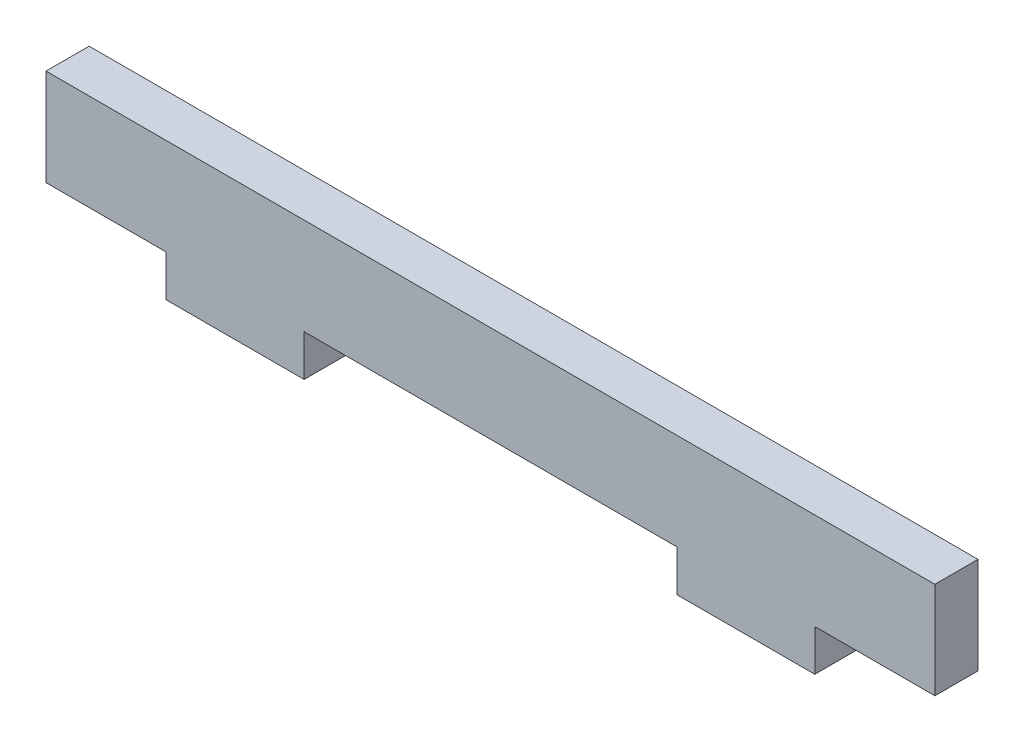
SolidWorks part; units mm, degrees
ref_plane "Front Plane" through (0, 0, 0) normal (0, 0, 1) x (1, 0, 0)
ref_plane "Top Plane" through (0, 0, 0) normal (0, 1, 0) x (1, 0, 0)
ref_plane "Right Plane" through (0, 0, 0) normal (1, 0, 0) x (0, 0, -1)
sketch "Sketch1" plane through (0, 0, 0) normal (0, 0, 1) x (1, 0, 0)
  line L0 (-26.8085, 9.7128) -> (-26.8085, 2.7128)
  line L1 (-26.8085, 2.7128) -> (-18.1085, 2.7128)
  line L2 (-18.1085, 2.7128) -> (-18.1085, -0.2872)
  line L3 (-18.1085, -0.2872) -> (-8.1085, -0.2872)
  line L4 (-8.1085, -0.2872) -> (-8.1085, 2.7128)
  line L5 (-8.1085, 2.7128) -> (18.8915, 2.7128)
  line L6 (18.8915, 2.7128) -> (18.8915, -0.2872)
  line L7 (18.8915, -0.2872) -> (28.8915, -0.2872)
  line L8 (28.8915, -0.2872) -> (28.8915, 2.7128)
  line L9 (28.8915, 2.7128) -> (37.5915, 2.7128)
  line L10 (37.5915, 2.7128) -> (37.5915, 9.7128)
  line L11 (37.5915, 9.7128) -> (-26.8085, 9.7128)
  dimension "D1" = 10
  dimension "D2" = 10
  dimension "D3" = 27
  dimension "D4" = 8.7
  dimension "D5" = 8.7
  dimension "D6" = 3
  dimension "D7" = 3
  dimension "D8" = 3
  dimension "D9" = 3
  dimension "D10" = 7
extrude "Boss-Extrude1" add sketch "Sketch1" along normal blind 3.125
